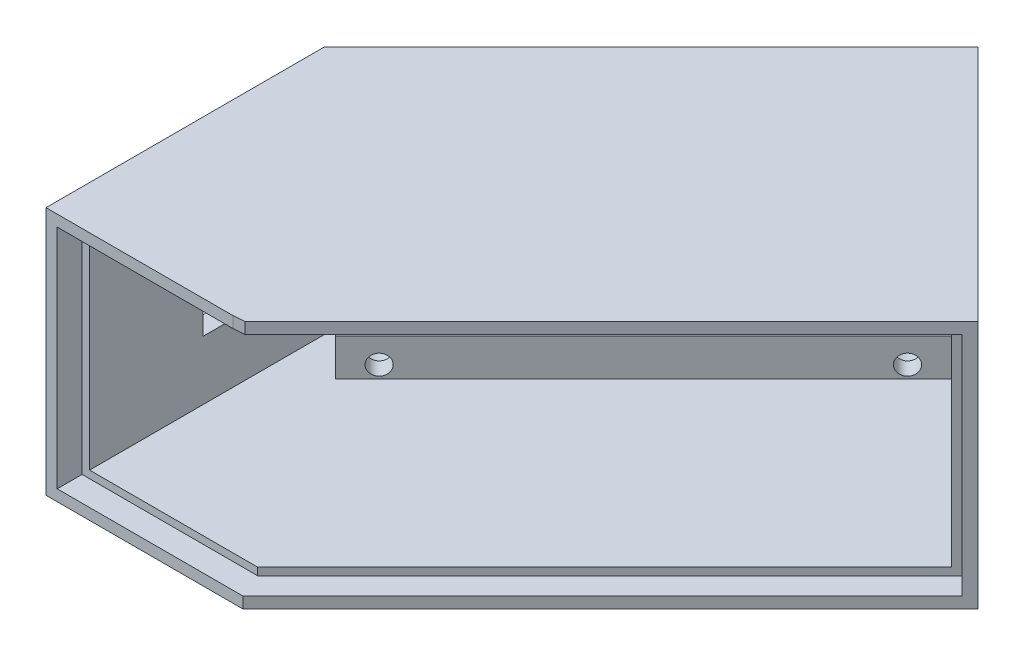
SolidWorks part; units mm, degrees
ref_plane "Спереди" through (0, 0, 0) normal (0, 0, 1) x (1, 0, 0)
ref_plane "Сверху" through (0, 0, 0) normal (0, 1, 0) x (1, 0, 0)
ref_plane "Справа" through (0, 0, 0) normal (1, 0, 0) x (0, 0, -1)
sketch "Sketch1" plane through (0, 0, 0) normal (0, 1, 0) x (1, 0, 0)
  line L0 (-43.3594, -5.3943) -> (-43.3594, 35.3164)
  line L1 (-43.3594, 35.3164) -> (9.115, 87.7907)
  line L2 (9.115, 87.7907) -> (44.4704, 52.4354)
  line L3 (44.4704, 52.4354) -> (-13.3594, -5.3943)
  line L4 (-13.3594, -5.3943) -> (-43.3594, -5.3943)
  dimension "D1" = 74.21
  dimension "D3" = 135
  dimension "D4" = 30
  dimension "D5" = 50
extrude "Boss-Extrude1" add sketch "Sketch1" along normal blind 40
shell "Shell1" thickness 3
sketch "Sketch6" plane through (-3.9825, 0, -3.9825) normal (0.7071, 0, 0.7071) x (0.7071, 0, -0.7071)
  line L0 (-13.2609, 38.2) -> (66.7227, 38.2)
  line L1 (-13.2609, 40) -> (-13.2609, 37) construction
  line L2 (66.7227, 38.2) -> (66.7227, 1.8)
  line L3 (66.7227, 1.8) -> (-13.2609, 1.8)
  line L4 (-13.2609, 3) -> (-13.2609, 0) construction
  line L5 (-13.2609, 40) -> (68.5227, 40) construction
  line L6 (-13.2609, 0) -> (68.5227, 0) construction
  line L7 (68.5227, 40) -> (68.5227, 0) construction
  line L8 (-13.2609, 38.2) -> (-13.2609, 40)
  line L9 (-13.2609, 40) -> (68.5227, 40)
  line L10 (68.5227, 40) -> (68.5227, 0)
  line L11 (68.5227, 0) -> (-13.2609, 0)
  line L12 (-13.2609, 0) -> (-13.2609, 1.8)
  dimension "D1" = 1.8
  dimension "D2" = 1.8
  dimension "D3" = 1.8
extrude "Boss-Extrude2" add sketch "Sketch6" along normal blind 4
sketch "Sketch7" plane through (0, 0, 5.3943) normal (0, 0, 1) x (1, 0, 0)
  line L0 (-13.3594, 1.8) -> (-41.5594, 1.8)
  line L1 (-41.5594, 1.8) -> (-41.5594, 38.2)
  line L2 (-41.5594, 38.2) -> (-13.3594, 38.2)
  line L3 (-43.3594, 40) -> (-43.3594, 0) construction
  line L4 (-13.3594, 38.2) -> (-13.3594, 40)
  line L5 (-13.3594, 40) -> (-43.3594, 40)
  line L6 (-43.3594, 40) -> (-43.3594, 0)
  line L7 (-43.3594, 0) -> (-13.3594, 0)
  line L8 (-13.3594, 0) -> (-13.3594, 1.8)
  dimension "D1" = 1.8
extrude "Boss-Extrude3" add sketch "Sketch7" along normal blind 4
sketch "Sketch8" plane through (0, 0, 0) normal (0, -1, 0) x (1, 0, 0)
  line L0 (-13.3594, 9.3943) -> (-11.7025, 9.3943)
  line L1 (-11.7025, 9.3943) -> (-10.5309, 8.2228)
  line L2 (-10.5309, 8.2228) -> (-13.3594, 5.3943)
  line L3 (-13.3594, 5.3943) -> (-13.3594, 9.3943)
  line L4 (-10.5309, 8.2228) -> (47.2988, -49.607) construction
extrude "Boss-Extrude4" add sketch "Sketch8" against normal up to surface (1.8 mm away) up to face at (16.3333, 1.8, -21.4699)
sketch "Sketch9" plane through (0, 40, 0) normal (0, 1, 0) x (1, 0, 0)
  line L0 (-13.3594, -5.3943) -> (-10.5309, -8.2228)
  line L1 (-10.5309, -8.2228) -> (-11.5537, -9.2455)
  line L2 (-11.5537, -9.2455) -> (-13.3594, -9.3943)
  line L3 (-13.3594, -9.3943) -> (-13.3594, -5.3943)
  line L4 (47.2988, 49.607) -> (-10.5309, -8.2228) construction
extrude "Boss-Extrude5" add sketch "Sketch9" against normal up to surface (1.8 mm away) up to face at (16.3333, 38.2, -21.4699)
sketch "Sketch10" plane through (-37.2165, 0, -37.2165) normal (0.7071, 0, 0.7071) x (0.7071, 0, -0.7071)
  line L0 (65.5227, 20) -> (-4.4446, 20) construction
  line L1 (65.5227, 37) -> (65.5227, 3) construction
  line L2 (-4.4446, 37) -> (-4.4446, 3) construction
  line L3 (60.5227, 35) -> (60.5227, 5) construction
  line L4 (68.5227, 40) -> (68.5227, 0) construction
  line L5 (0.5227, 35) -> (0.5227, 5) construction
  line L6 (60.5227, 35) -> (0.5227, 35) construction
  circle A0 centre (60.5227, 35) radius 1.6
  circle A1 centre (60.5227, 5) radius 1.6
  circle A2 centre (0.5227, 35) radius 1.6
  circle A3 centre (0.5227, 5) radius 1.6
  point P8 (60.5227, 20)
  point P11 (68.5227, 20)
  dimension "D3" = 3.2
  dimension "D1" = 30
  dimension "D2" = 8
  dimension "D4" = 60
extrude "Cut-Extrude6" cut sketch "Sketch10" against normal through all
sketch "Sketch11" plane through (-40.3594, 0, 0) normal (1, 0, 0) x (0, 0, -1)
  line L0 (19.2076, 37) -> (19.2076, 3) construction
  line L1 (34.0737, 37) -> (-5.3943, 37) construction
  line L2 (34.0737, 3) -> (-5.3943, 3) construction
  line L4 (12.8076, 12.5) -> (25.6076, 12.5)
  line L5 (12.8076, 12.5) -> (12.8076, 27.5)
  line L6 (12.8076, 27.5) -> (25.6076, 27.5)
  line L7 (25.6076, 12.5) -> (25.6076, 27.5)
  line L8 (12.8076, 12.5) -> (25.6076, 27.5) construction
  line L9 (12.8076, 27.5) -> (25.6076, 12.5) construction
  point P6 (19.2076, 20)
  dimension "D1" = 15
  dimension "D2" = 12.8
extrude "Cut-Extrude7" cut sketch "Sketch11" against normal up to surface (3 mm away) up to face at (-43.3594, 20, -12.961)
sketch "Sketch12" plane through (-37.2165, 0, -37.2165) normal (0.7071, 0, 0.7071) x (0.7071, 0, -0.7071)
  line L0 (65.5227, 37) -> (-4.4446, 3) construction
  line L1 (-4.4446, 37) -> (-4.4446, 3) construction
  line L3 (65.5227, 3) -> (-4.4446, 3)
  line L4 (65.5227, 3) -> (65.5227, 37)
  line L5 (65.5227, 37) -> (-4.4446, 37)
  line L6 (-4.4446, 3) -> (-4.4446, 37)
  line L7 (65.5227, 3) -> (-4.4446, 37) construction
  line L8 (65.5227, 37) -> (-4.4446, 3) construction
  circle A0 centre (0.5227, 35) radius 1.6
  circle A1 centre (60.5227, 35) radius 1.6
  circle A2 centre (60.5227, 5) radius 1.6
  circle A3 centre (0.5227, 5) radius 1.6
  point P5 (30.539, 20)
extrude "Boss-Extrude7" add sketch "Sketch12" along normal blind 10
sketch "Sketch13" plane through (-39.3379, 0, -39.3379) normal (-0.7071, 0, -0.7071) x (-0.7071, 0, 0.7071)
  circle A0 centre (-0.5227, 35) radius 3.1
  circle A1 centre (-0.5227, 5) radius 3.1
  circle A2 centre (-60.5227, 5) radius 3.1
  circle A3 centre (-60.5227, 35) radius 3.1
  dimension "D1" = 6.2
extrude "Cut-Extrude9" cut sketch "Sketch13" against normal blind 10
sketch "Sketch14" plane through (-30.1455, 0, -30.1455) normal (0.7071, 0, 0.7071) x (0.7071, 0, -0.7071)
  line L0 (-4.4446, 37) -> (65.5227, 3) construction
  line L1 (-4.4446, 37) -> (-4.4446, 3) construction
  line L2 (65.5227, 9) -> (-4.4446, 9)
  line L3 (65.5227, 9) -> (65.5227, 31)
  line L4 (65.5227, 31) -> (-4.4446, 31)
  line L5 (-4.4446, 9) -> (-4.4446, 31)
  line L6 (65.5227, 9) -> (-4.4446, 31) construction
  line L7 (65.5227, 31) -> (-4.4446, 9) construction
  point P4 (30.539, 20)
  dimension "D1" = 22
extrude "Cut-Extrude10" cut sketch "Sketch14" against normal blind 10
